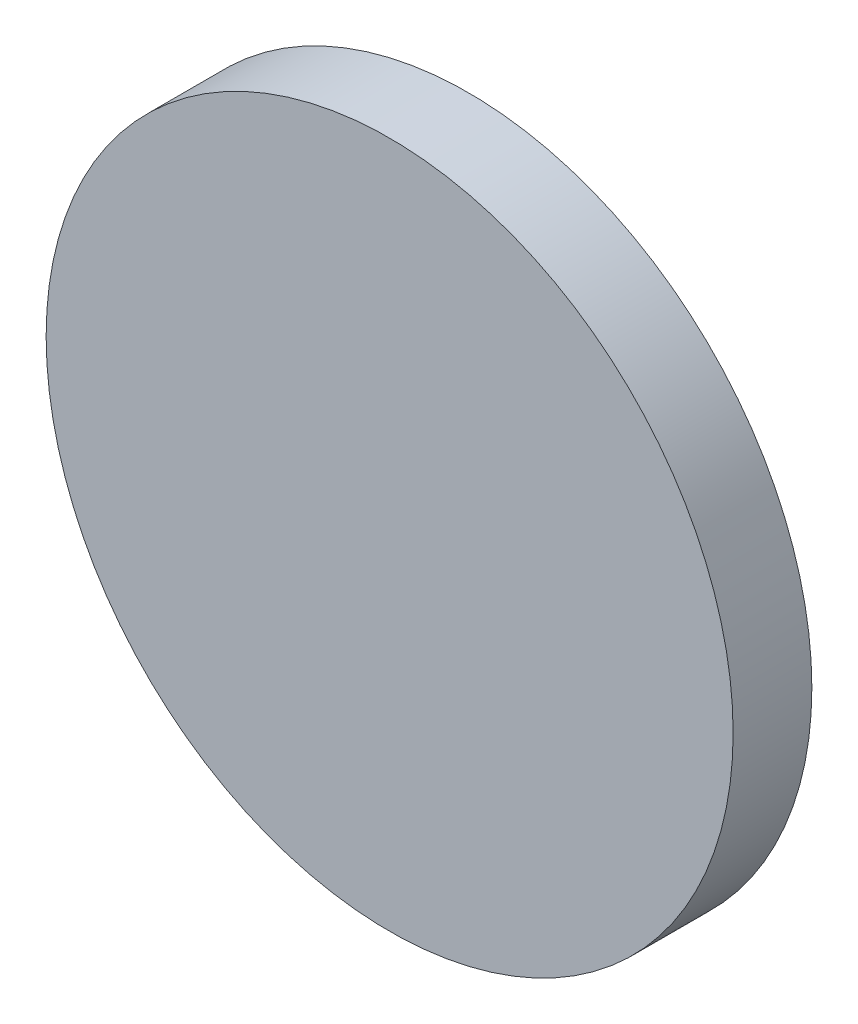
SolidWorks part; units mm, degrees
ref_plane "Front Plane" through (0, 0, 0) normal (0, 0, 1) x (1, 0, 0)
ref_plane "Top Plane" through (0, 0, 0) normal (0, 1, 0) x (1, 0, 0)
ref_plane "Right Plane" through (0, 0, 0) normal (1, 0, 0) x (0, 0, -1)
sketch "Sketch1" plane through (0, 0, 0) normal (0, 0, 1) x (1, 0, 0)
  circle A0 centre (0, 0) radius 43.6326
extrude "Boss-Extrude1" add sketch "Sketch1" along normal blind 10
